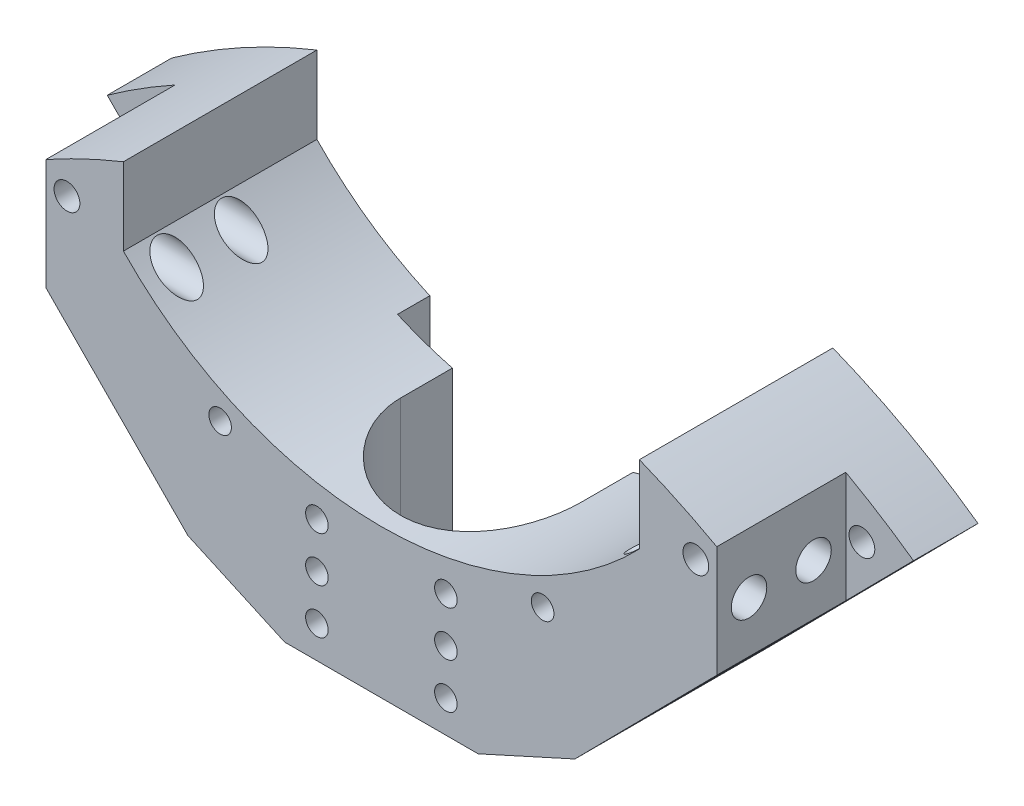
SolidWorks part; units mm, degrees
ref_plane "Front Plane" through (0, 0, 0) normal (0, 0, 1) x (1, 0, 0)
ref_plane "Top Plane" through (0, 0, 0) normal (0, 1, 0) x (1, 0, 0)
ref_plane "Right Plane" through (0, 0, 0) normal (1, 0, 0) x (0, 0, -1)
sketch "Sketch1" plane through (0, 0, 0) normal (0, 0, 1) x (1, 0, 0)
  line L0 (0, -107.5) -> (0, 0) construction
  line L1 (-40, -7.719) -> (-40, -19.719)
  line L2 (-40, -19.719) -> (40, -19.719) construction
  line L3 (40, -19.719) -> (40, -7.719)
  line L4 (40, -7.719) -> (-40, -7.719) construction
  line L5 (-62.5, -20.0357) -> (-30, -52.9137)
  line L6 (-15, -59.719) -> (15, -59.719)
  line L7 (30, -52.9137) -> (62.5, -20.0357)
  line L8 (62.5, -20.0357) -> (-62.5, -20.0357) construction
  line L9 (-46.0085, -36.719) -> (46.0085, -36.719) construction
  line L10 (-30, -52.9137) -> (-15, -59.719)
  line L11 (30, -52.9137) -> (15, -59.719)
  line L12 (-30, -52.9137) -> (30, -52.9137) construction
  circle A0 centre (0, -107.5) radius 107.5 construction
  arc A1 (-40, -19.719) -> (40, -19.719) centre (0, 18.8398) ccw
  arc A2 (-62.5, -20.0357) -> (-40, -7.719) centre (0, -107.5) cw
  arc A3 (40, -7.719) -> (62.5, -20.0357) centre (0, -107.5) cw
  point P10 (0, -59.719)
  point P19 (0, -52.9137)
  point P21 (-45.2301, -40.6783)
  point P22 (-34.9141, -49.1529)
  point P23 (0, -36.719)
  point P24 (25, -53.2025)
  point P25 (25, -50.2352)
  point P26 (30, -51.9102)
  dimension "D1" = 215
  dimension "D2" = 80
  dimension "D3" = 12
  dimension "D4" = 125
  dimension "D5" = 40
  dimension "D6" = 17
  dimension "D7" = 30
  dimension "D8" = 60
extrude "Boss-Extrude1" add sketch "Sketch1" along normal blind 30
sketch "Sketch2" plane through (0, 0, 30) normal (0, 0, 1) x (1, 0, 0)
  line L0 (0, -16.5) -> (0, 16.5) construction
  line L1 (-52, -13.4136) -> (-62.5, -13.4136)
  line L2 (-52, -13.4136) -> (-52, -42.6766)
  line L3 (-52, -42.6766) -> (-62.5, -42.6766)
  line L4 (-62.5, -13.4136) -> (-62.5, -42.6766)
  line L5 (52, -42.6766) -> (62.5, -42.6766)
  line L6 (62.5, -13.4136) -> (62.5, -42.6766)
  line L7 (52, -13.4136) -> (62.5, -13.4136)
  line L8 (52, -13.4136) -> (52, -42.6766)
  line L9 (-40, -19.719) -> (-40, -7.719) construction
  arc A0 (-40, -7.719) -> (-62.5, -20.0357) centre (0, -107.5) ccw construction
  dimension "D1" = 12
extrude "Cut-Extrude1" cut sketch "Sketch2" against normal blind 20
chamfer "Chamfer1" [suppressed] distance 10 angle 60
sketch "Sketch3" plane through (0, -59.719, 0) normal (0, -1, 0) x (1, 0, 0)
  line L0 (0, 13) -> (0, 0) construction
  line L1 (-14, 13) -> (-14, 0)
  line L2 (-15, 0) -> (15, 0) construction
  line L3 (-14, 0) -> (14, 0)
  line L4 (14, 0) -> (14, 13)
  line L5 (-14, 13) -> (14, 13) construction
  arc A0 (14, 13) -> (-14, 13) centre (0, 13) ccw
  point P1 (0, 0)
  dimension "D1" = 28
  dimension "D2" = 13
extrude "Cut-Extrude2" cut sketch "Sketch3" against normal through all
sketch "Sketch4" plane through (0, 0, 0) normal (1, 0, 0) x (0, 0, -1)
  line L0 (-30, -7.719) -> (0, -7.719) construction
  line L2 (-10, -13.4136) -> (-10, -20.0357) construction
  circle A0 centre (-15, -22.719) radius 2.75
  circle A1 centre (-25, -22.719) radius 2.75
  dimension "D3" = 5.5
  dimension "D1" = 15
  dimension "D2" = 5
  dimension "D4" = 2
extrude "Cut-Extrude3" cut sketch "Sketch4" against normal through all both and the other way through all
sketch "Sketch5" [suppressed] plane through (47.5, 0, 0) normal (1, 0, 0) x (0, 0, -1)
  line L0 (-30, -26.6599) -> (-24.9079, -26.6599)
  line L1 (-20, -11.0635) -> (-20, -34.747) construction
  line L2 (-20, -22.6153) -> (-20, -8.7579)
  line L3 (-22.8868, -8.7579) -> (0, -8.7579) construction
  line L4 (-20, -8.7579) -> (-22.8868, -8.7579)
  line L5 (-22.8868, -8.7579) -> (-30, -26.6599)
  arc A0 (-20, -22.6153) -> (-24.9079, -26.6599) centre (-20, -27.6153) ccw
  dimension "D1" = 10
extrude "Cut-Extrude4" [suppressed] cut sketch "Sketch5" against normal through all both
sketch "Sketch6" plane through (0, 0, 10) normal (0, 0, 1) x (1, 0, 0)
  line L0 (-54.5, -21.5357) -> (54.5, -21.5357) construction
  line L1 (0, -21.5357) -> (0, 0) construction
  line L2 (-48.75, -16.719) -> (48.75, -16.719) construction
  line L3 (0, -16.719) -> (0, -21.5357) construction
  circle A0 centre (-54.5, -21.5357) radius 2
  circle A1 centre (54.5, -21.5357) radius 2
  circle A2 centre (-48.75, -16.719) radius 2
  circle A3 centre (48.75, -16.719) radius 2
  dimension "D3" = 4
  dimension "D1" = 109
  dimension "D2" = 1.5
  dimension "D4" = 97.5
  dimension "D5" = 9
extrude "Cut-Extrude5" cut sketch "Sketch6" against normal through all both and the other way through all
sketch "Sketch7" plane through (0, 0, 0) normal (0, 1, 0) x (1, 0, 0)
  line L0 (0, 0) -> (0, -12) construction
  line L1 (-31, -5) -> (31, -5)
  line L2 (-35, -9) -> (-35, -15)
  line L3 (-31, -19) -> (31, -19)
  line L4 (35, -9) -> (35, -15)
  line L5 (-35, -5) -> (35, -19) construction
  line L6 (-35, -19) -> (35, -5) construction
  arc A0 (31, -5) -> (35, -9) centre (31, -9) cw
  arc A1 (31, -19) -> (35, -15) centre (31, -15) ccw
  arc A2 (-35, -15) -> (-31, -19) centre (-31, -15) ccw
  arc A3 (-31, -5) -> (-35, -9) centre (-31, -9) ccw
  point P0 (0, -12)
  dimension "D4" = 4
  dimension "D1" = 12
  dimension "D2" = 14
  dimension "D3" = 70
extrude "Cut-Extrude6" [suppressed] cut sketch "Sketch7" against normal blind 33
sketch "Sketch8" [suppressed] plane through (0, -33, 0) normal (0, 1, 0) x (1, 0, 0)
  line L0 (-27.5, -12) -> (27.5, -12) construction
  line L1 (0, -12) -> (0, 0) construction
  circle A0 centre (-27.5, -12) radius 4
  circle A1 centre (27.5, -12) radius 4
  dimension "D3" = 8
  dimension "D1" = 12
  dimension "D2" = 55
extrude "Cut-Extrude7" [suppressed] cut sketch "Sketch8" against normal through all
sketch "Sketch9" plane through (0, 0, 0) normal (0, 1, 0) x (1, 0, 0)
  line L0 (-14, 0) -> (-40, 0) construction
  line L1 (-22.5, 5) -> (22.5, 5)
  line L2 (-22.5, 5) -> (-22.5, -5)
  line L3 (-22.5, -5) -> (22.5, -5)
  line L4 (22.5, 5) -> (22.5, -5)
  line L5 (-22.5, 5) -> (22.5, -5) construction
  line L6 (-22.5, -5) -> (22.5, 5) construction
  point P0 (0, 0)
  dimension "D1" = 5
  dimension "D2" = 45
extrude "Cut-Extrude8" cut sketch "Sketch9" against normal through all
sketch "Sketch10" plane through (0, 0, 30) normal (0, 0, 1) x (1, 0, 0)
  line L0 (-25, -35.0357) -> (25, -35.0357) construction
  line L1 (0, -35.0357) -> (0, 0) construction
  circle A0 centre (-25, -35.0357) radius 1.75
  circle A1 centre (25, -35.0357) radius 1.75
  dimension "D2" = 3.5
  dimension "D1" = 50
  dimension "D3" = 15
extrude "Cut-Extrude9" cut sketch "Sketch10" against normal through all
sketch "Sketch11" plane through (0, 0, 30) normal (0, 0, 1) x (1, 0, 0)
  circle A3 centre (-25, -35.0357) radius 4.75
  circle A4 centre (-25, -35.0357) radius 4.75
  circle A6 centre (25, -35.0357) radius 4.75
  circle A7 centre (25, -35.0357) radius 4.75
  dimension "D1" = 3
  dimension "D2" = 3
extrude "Cut-Extrude10" [suppressed] cut sketch "Sketch11" against normal blind 22
sketch "Sketch12" plane through (0, 0, 30) normal (0, 0, 1) x (1, 0, 0)
  line L0 (-10, -54.719) -> (10, -54.719) construction
  line L1 (0, -54.719) -> (0, 0) construction
  line L2 (-15, -59.719) -> (15, -59.719) construction
  circle A0 centre (-10, -54.719) radius 1.75
  circle A1 centre (10, -54.719) radius 1.75
  dimension "D3" = 3.5
  dimension "D1" = 20
  dimension "D2" = 5
extrude "Cut-Extrude11" cut sketch "Sketch12" against normal through all
pattern_linear "LPattern1" count 3 spacing 7 along (0, 1, 0) of "Cut-Extrude11"
sketch "Sketch13" plane through (0, 0, 0) normal (0, 0, -1) x (-1, 0, 0)
  circle A0 centre (-48.75, -16.719) radius 4
  circle A1 centre (48.75, -16.719) radius 4
  dimension "D1" = 8
extrude "Cut-Extrude12" cut sketch "Sketch13" against normal blind 5
